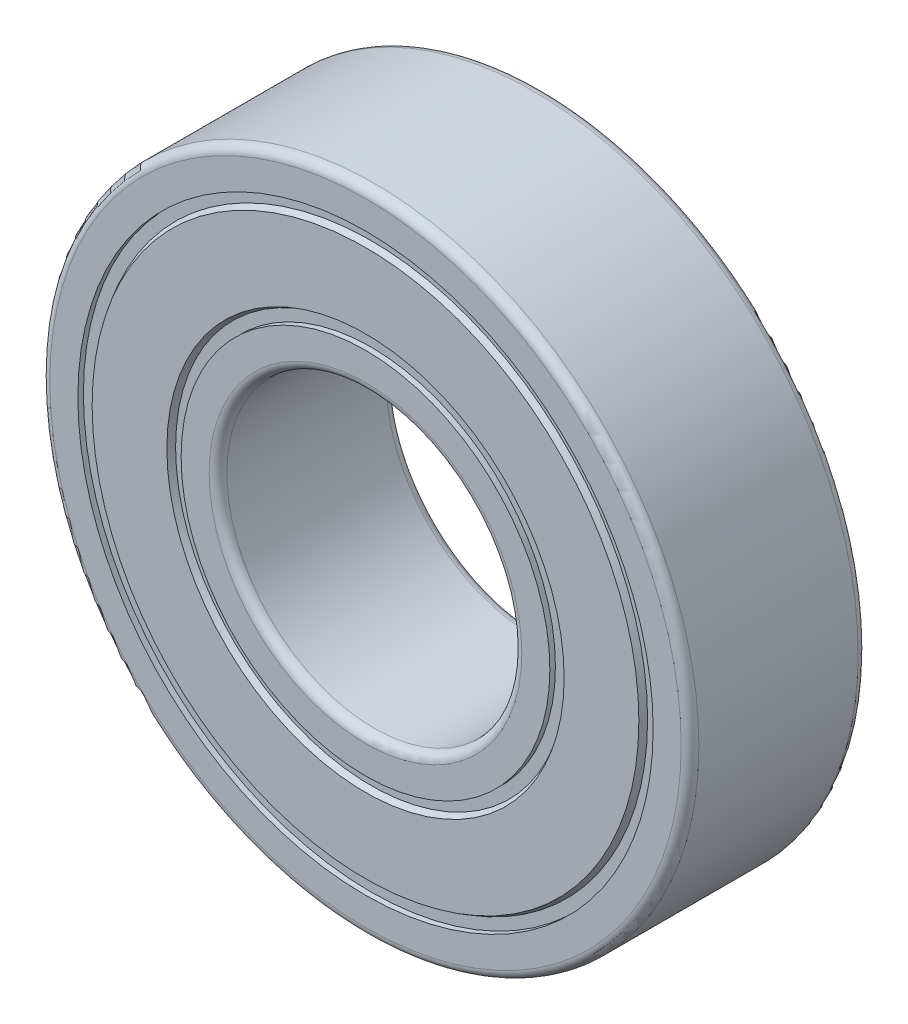
SolidWorks part; units mm, degrees
ref_plane "Plane1" through (0, 0, 0) normal (0, 0, 1) x (1, 0, 0)
ref_plane "Plane2" through (0, 0, 0) normal (0, 1, 0) x (1, 0, 0)
ref_plane "Plane3" through (0, 0, 0) normal (1, 0, 0) x (0, 0, -1)
sketch "Sketch2" plane through (0, 0, 0) normal (0, 1, 0) x (1, 0, 0)
  line L0 (0, -19) -> (0, 31) construction
  line L1 (-9.75, 0) -> (-9.75, -0.1875)
  line L2 (-5.3, -6) -> (-6.25, -6)
  line L3 (-5, -5.7) -> (-5, -0.3)
  line L4 (-5.3, 0) -> (-6.25, 0)
  line L5 (-11, -5.7) -> (-11, -0.3)
  line L6 (-9.75, -6) -> (-9.75, -5.8125)
  line L7 (-9.75, 0) -> (-10.7, 0)
  line L8 (-9.75, -6) -> (-10.7, -6)
  line L9 (-11, -3) -> (-5, -3) construction
  line L10 (-9.75, -0.1875) -> (-9.375, -0.1875)
  line L11 (-9.75, -5.8125) -> (-9.375, -5.8125)
  line L12 (-9.375, -0.1875) -> (-9.2667, 0)
  line L13 (-9.375, -5.8125) -> (-9.2667, -6)
  line L14 (-6.25, 0) -> (-6.25, -0.1875)
  line L15 (-6.25, -6) -> (-6.25, -5.8125)
  line L16 (-9.2667, -6) -> (-6.7333, -6)
  line L17 (-9.2667, 0) -> (-6.7333, 0)
  line L18 (-6.25, -0.1875) -> (-6.625, -0.1875)
  line L19 (-6.25, -5.8125) -> (-6.625, -5.8125)
  line L20 (-6.625, -0.1875) -> (-6.7333, 0)
  line L21 (-6.625, -5.8125) -> (-6.7333, -6)
  line L26 (-5.3, -6) -> (-5.2, -6) construction
  line L27 (-5.3, 0) -> (-5.2, 0) construction
  line L28 (-5, -5.8) -> (-5, -5.7) construction
  line L29 (-5, -0.2) -> (-5, -0.3) construction
  line L30 (-11, -5.7) -> (-11, -5.8) construction
  line L31 (-10.8, -6) -> (-10.7, -6) construction
  line L32 (-11, -0.3) -> (-11, -0.2) construction
  line L33 (-10.8, 0) -> (-10.7, 0) construction
  arc A0 (-11, -0.3) -> (-10.7, 0) centre (-10.7, -0.3) cw
  arc A1 (-11, -5.7) -> (-10.7, -6) centre (-10.7, -5.7) ccw
  arc A2 (-5, -5.7) -> (-5.3, -6) centre (-5.3, -5.7) cw
  arc A3 (-5.3, 0) -> (-5, -0.3) centre (-5.3, -0.3) cw
  arc A4 (-5, -5.8) -> (-5.2, -6) centre (-5.2, -5.8) cw construction
  arc A5 (-5, -0.2) -> (-5.2, 0) centre (-5.2, -0.2) ccw construction
  arc A6 (-10.8, -6) -> (-11, -5.8) centre (-10.8, -5.8) cw construction
  arc A7 (-10.8, 0) -> (-11, -0.2) centre (-10.8, -0.2) ccw construction
  circle A8 centre (-8, -3) radius 1.875
  dimension "r" = 0.3
  dimension "BallDia" = 3.75
  dimension "B" = 6
  dimension "ID" = 10
  dimension "OD" = 22
  dimension "OR-ID" = 19.5
  dimension "IR-OD" = 12.5
  dimension "D4" = 5.625
  dimension "D5" = 5.625
  dimension "Shield-OD" = 0.375
  dimension "D9" = 60
  dimension "Shield-ID" = 0.375
  dimension "D11" = 60
revolve "Base-Revolve" add sketch "Sketch2" angle 360 about L0
equation "\"D5@Sketch2\"=\"B@Sketch2\" * .9375"
equation "\"D4@Sketch2\" = \"D5@Sketch2\""
equation "\"BallDia@Sketch2\" = \"B@Sketch2\" * .625"
equation "\"Shield-OD@Sketch2\" = (\"OD@Sketch2\"-\"ID@Sketch2\") * 0.03125"
equation "\"Shield-ID@Sketch2\" = \"Shield-OD@Sketch2\""
